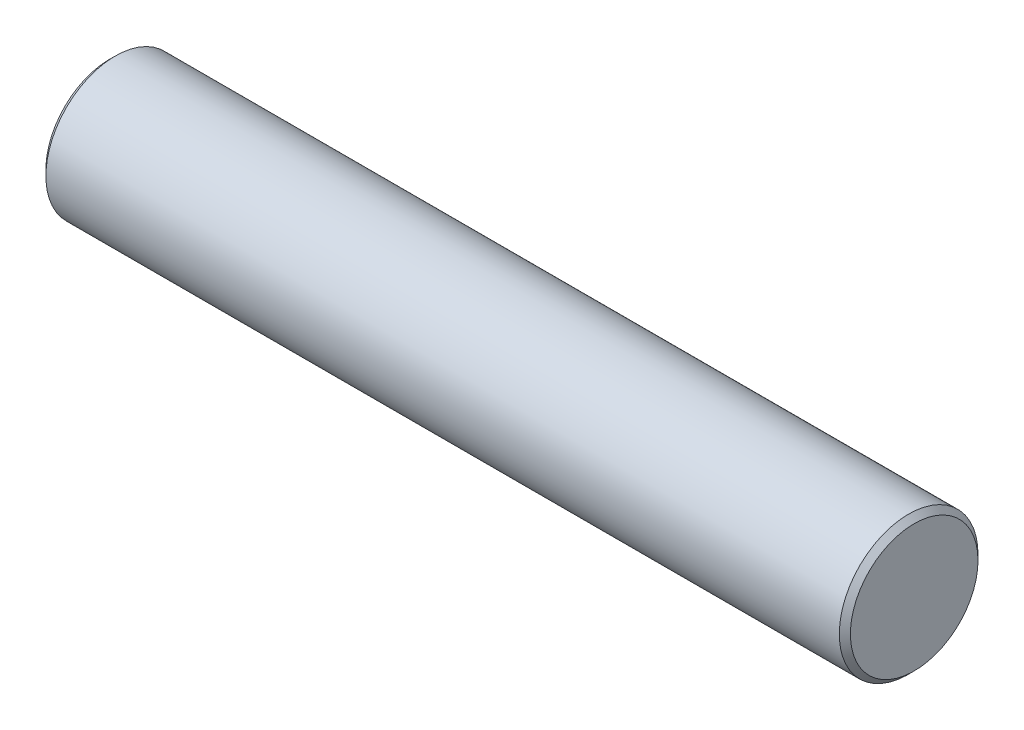
SolidWorks part; units mm, degrees
ref_plane "Front Plane" through (0, 0, 0) normal (0, 0, 1) x (1, 0, 0)
ref_plane "Top Plane" through (0, 0, 0) normal (0, 1, 0) x (1, 0, 0)
ref_plane "Right Plane" through (0, 0, 0) normal (1, 0, 0) x (0, 0, -1)
sketch "Sketch1" plane through (0, 0, 0) normal (1, 0, 0) x (0, 0, -1)
  circle A0 centre (0, 0) radius 12.5
  dimension "D1" = 25
extrude "Boss-Extrude1" add sketch "Sketch1" along normal blind 145 contours A0
chamfer "Chamfer1" distance 1 angle 45 2 edges at (0, 0, -12.5) (145, 0, -12.5)
